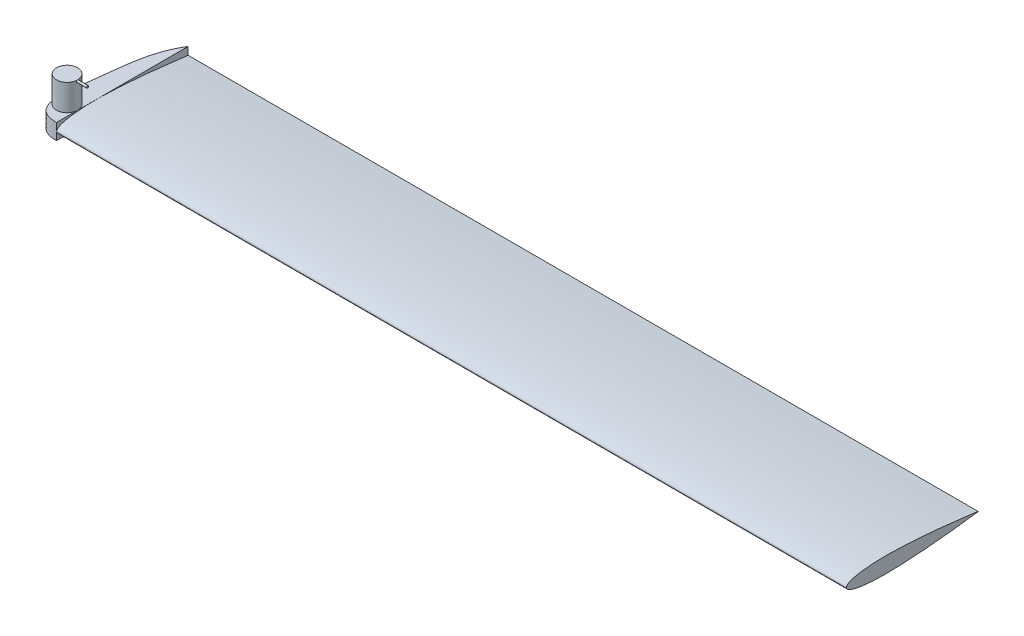
SolidWorks part; units mm, degrees
ref_plane "Ön Düzlem" through (0, 0, 0) normal (0, 0, 1) x (1, 0, 0)
ref_plane "Üst Düzlem" through (0, 0, 0) normal (0, 1, 0) x (1, 0, 0)
ref_plane "Sağ Düzlem" through (0, 0, 0) normal (1, 0, 0) x (0, 0, -1)
sketch "Sketch1" plane through (0, 0, 0) normal (1, 0, 0) x (0, 0, -1)
  line L0 (305.5, 117) -> (1527.5, 117) construction
  line L1 (124.9958, 7.6975) -> (124.9958, 7.3551)
  spline S0 degree 3 poles (124.9958, 7.6975) (121.5494, 8.133) (115.7079, 8.8711) (106.6128, 10.0012) (98.7767, 10.9001) (91.0104, 11.7181) (84.4662, 12.3744) (77.1231, 13.0109) (70.0969, 13.6616) (63.2322, 14.0383) (56.9512, 14.4586) (50.1831, 14.7448) (43.7131, 14.9288) (38.0167, 14.9868) (31.8671, 14.9642) (25.9611, 14.7642) (20.4185, 14.3189) (16.0809, 13.9021) (11.9484, 13.2767) (7.872, 12.4387) (4.5515, 11.4816) (1.9351, 10.1896) (0.4198, 8.8678) (-0.1163, 7.6764) (0.2285, 6.5757) (1.0921, 5.3828) (3.1213, 4.1827) (5.8339, 3.1224) (8.9694, 2.338) (12.4549, 1.6356) (16.398, 1.0576) (20.4074, 0.6193) (24.9405, 0.3185) (28.9969, 0.0979) (33.6404, 0.065) (37.6198, -0.0088) (42.1302, 0.0152) (46.8255, 0.1281) (52.0592, 0.3082) (57.5703, 0.566) (63.0666, 0.9035) (68.7816, 1.2736) (74.2411, 1.7012) (79.3321, 2.132) (83.7651, 2.5258) (88.3339, 3.015) (93.4519, 3.4955) (98.4485, 4.0307) (103.3599, 4.5597) (107.5347, 5.0511) (112.036, 5.6526) (116.8989, 6.2051) (121.1853, 6.8982) (124.0349, 7.1356) (124.8716, 7.3267) (124.9958, 7.3551) knots 0 0 0 0 0.04091 0.069341 0.107932 0.133796 0.161307 0.185386 0.220598 0.244394 0.266344 0.294731 0.324163 0.342565 0.361816 0.396586 0.412117 0.427295 0.447896 0.461301 0.476285 0.488528 0.495262 0.499816 0.502761 0.50837 0.516837 0.529992 0.542689 0.554812 0.57187 0.589596 0.602296 0.625369 0.637421 0.656977 0.672241 0.690534 0.712285 0.733913 0.755504 0.777134 0.801357 0.819993 0.837304 0.853767 0.874103 0.897841 0.912946 0.932278 0.947342 0.966429 0.989896 0.9985 1 1 1 1
extrude "Boss-Extrude1" add sketch "Sketch1" along normal blind 750
sketch "Sketch2" plane through (0, 0, 0) normal (0, 1, 0) x (1, 0, 0)
  line L0 (0, 124.9958) -> (0, -0.0001) construction
  line L1 (0, -0.0001) -> (750, -0.0001) construction
  line L2 (0, 124.9958) -> (0, -0.0001)
  circle A0 centre (-10, 19.9999) radius 10
  spline S0 degree 2 poles (0, -0.0001) (-19.65, -0.3381) (-20, 19.9999) knots 0 0 0 1 1 1
  spline S1 degree 3 poles (-20, 19.9999) (-20.2565, 33.6052) (-15.1417, 69.221) (-12.6667, 105.0115) (0, 124.9958) knots 0 0 0 0 0.363919 1 1 1 1
  dimension "D1" = 20
  dimension "D2" = 20
extrude "Boss-Extrude4" add sketch "Sketch2" along normal blind 15 contours S0 L2 A0 | S1 A0 L2 | S0 A0
sketch "Sketch3" plane through (0, 15, 0) normal (0, 1, 0) x (1, 0, 0)
  line L0 (0, 124.9958) -> (0, -0.0001) construction
  circle A0 centre (-10, 20) radius 10
  dimension "D1" = 20
  dimension "D2" = 20
extrude "Boss-Extrude5" add sketch "Sketch3" along normal blind 25
sketch "Sketch4" plane through (0, 0, 0) normal (1, 0, 0) x (0, 0, -1)
  line L0 (30, 40) -> (10, 40) construction
  line L1 (10, 40) -> (10, 15) construction
  circle A0 centre (20, 39) radius 1
  dimension "D1" = 2
  dimension "D2" = 10
extrude "Boss-Extrude6" add sketch "Sketch4" along normal blind 9.5 and the other way up to next (9.5 mm away)
